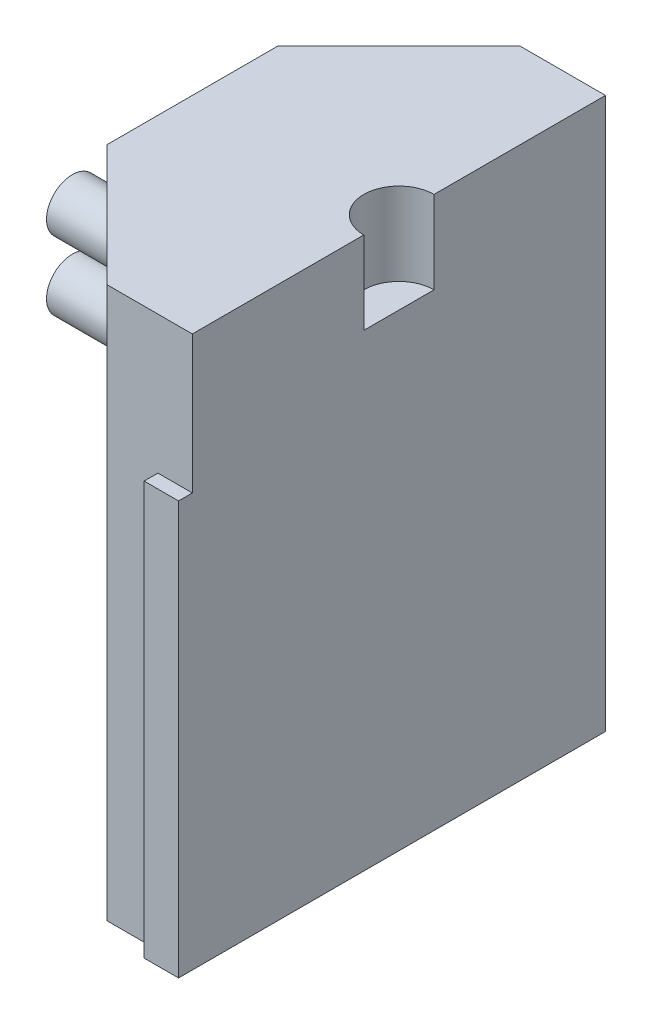
SolidWorks part; units mm, degrees
ref_plane "Front Plane" through (0, 0, 0) normal (0, 0, 1) x (1, 0, 0)
ref_plane "Top Plane" through (0, 0, 0) normal (0, 1, 0) x (1, 0, 0)
ref_plane "Right Plane" through (0, 0, 0) normal (1, 0, 0) x (0, 0, -1)
sketch "Sketch1" plane through (0, 0, 0) normal (0, 1, 0) x (1, 0, 0)
  line L0 (12.4264, -30) -> (30, -12.4264)
  line L1 (30, 12.4264) -> (12.4264, 30)
  line L2 (12.4264, 30) -> (-12.4264, 30)
  line L3 (-12.4264, 30) -> (-30, 12.4264)
  line L4 (-30, 12.4264) -> (-30, -12.4264)
  line L5 (-30, -12.4264) -> (-12.4264, -30)
  line L6 (-12.4264, -30) -> (12.4264, -30)
  line L7 (30, -12.4264) -> (30, 12.4264)
  circle A0 centre (0, 0) radius 30 construction
  point P1 (36.2246, 15.0047)
  point P12 (30, 12.4264)
  dimension "D1" = 60
extrude "Boss-Extrude1" add sketch "Sketch1" along normal blind 80
ref_plane "Plane1" through (0, 40, 0) normal (0, 1, 0) x (1, 0, 0)
sketch "Sketch3" plane through (0, 40, 0) normal (0, 1, 0) x (1, 0, 0)
  line L0 (40, 25) -> (10, 5.1)
  line L1 (10, 5.1) -> (10, -5.1)
  line L2 (10, -5.1) -> (40, -25)
  line L3 (40, 25) -> (40, -25)
  point P2 (10, 0)
  point P5 (40, 23.2344)
  dimension "D1" = 10.2
  dimension "D2" = 30
  dimension "D3" = 10
  dimension "D4" = 50
extrude "Cut-Extrude1" cut sketch "Sketch3" against normal blind 1.1 and the other way blind 1.1
mirror "Mirror1" about plane through (0, 0, 0) normal (1, 0, 0) of "Cut-Extrude1"
sketch "Sketch4" plane through (0, 80, 0) normal (0, 1, 0) x (1, 0, 0)
  line L0 (12.4264, 30) -> (-12.4264, 30) construction
  line L1 (0, 30) -> (30, 30)
  line L2 (0, 30) -> (0, -30)
  line L3 (0, -30) -> (30, -30)
  line L4 (30, 30) -> (30, -30)
  line L5 (-12.4264, -30) -> (12.4264, -30) construction
  line L6 (30, -12.4264) -> (30, 12.4264) construction
extrude "Cut-Extrude2" cut sketch "Sketch4" against normal through all
sketch "Sketch5" plane through (0, 80, 0) normal (0, 1, 0) x (1, 0, 0)
  line L0 (0, 30) -> (0, -30) construction
  circle A0 centre (0, 0) radius 5.1
  dimension "D1" = 10.2
extrude "Cut-Extrude3" cut sketch "Sketch5" against normal blind 12
sketch "Sketch6" plane through (-30, 0, 0) normal (-1, 0, 0) x (0, 0, 1)
  line L0 (12.4264, 80) -> (12.4264, 41.1) construction
  line L1 (-12.4264, 0) -> (12.4264, 0) construction
  line L2 (-5, 20) -> (5, 20)
  line L3 (-5, 20) -> (-5, 10)
  line L4 (-5, 10) -> (5, 10)
  line L5 (5, 20) -> (5, 10)
  line L6 (-12.4264, 80) -> (12.4264, 80) construction
  circle A0 centre (12.4264, 70) radius 3.75
  circle A1 centre (12.4264, 60) radius 3.75
  point P10 (0, 10)
  dimension "D5" = 7.5
  dimension "D1" = 10
  dimension "D2" = 10
  dimension "D3" = 10
  dimension "D4" = 10
extrude "Boss-Extrude2" add sketch "Sketch6" along normal blind 5 and the other way blind 12
sketch "Sketch7" plane through (0, 0, 30) normal (0, 0, 1) x (1, 0, 0)
  line L0 (0, 0) -> (0, 80) construction
  line L1 (0, 0) -> (-5, 0)
  line L2 (0, 0) -> (0, 60)
  line L3 (0, 60) -> (-5, 60)
  line L4 (-5, 0) -> (-5, 60)
  line L5 (-12.4264, 0) -> (0, 0) construction
  point P6 (-7.1662, 63.8244)
  point P7 (-5, 0)
  dimension "D1" = 5
  dimension "D2" = 60
extrude "Boss-Extrude3" add sketch "Sketch7" along normal blind 2
sketch "Sketch8" plane through (0, 0, 30) normal (0, 0, 1) x (1, 0, 0)
  line L1 (-30, 0) -> (-24.9, 0)
  line L2 (-30, 0) -> (-30, 5.1)
  line L3 (-30, 5.1) -> (-24.9, 5.1)
  line L4 (-24.9, 0) -> (-24.9, 5.1)
  dimension "D1" = 5.1
extrude "Cut-Extrude4" cut sketch "Sketch8" against normal through all
